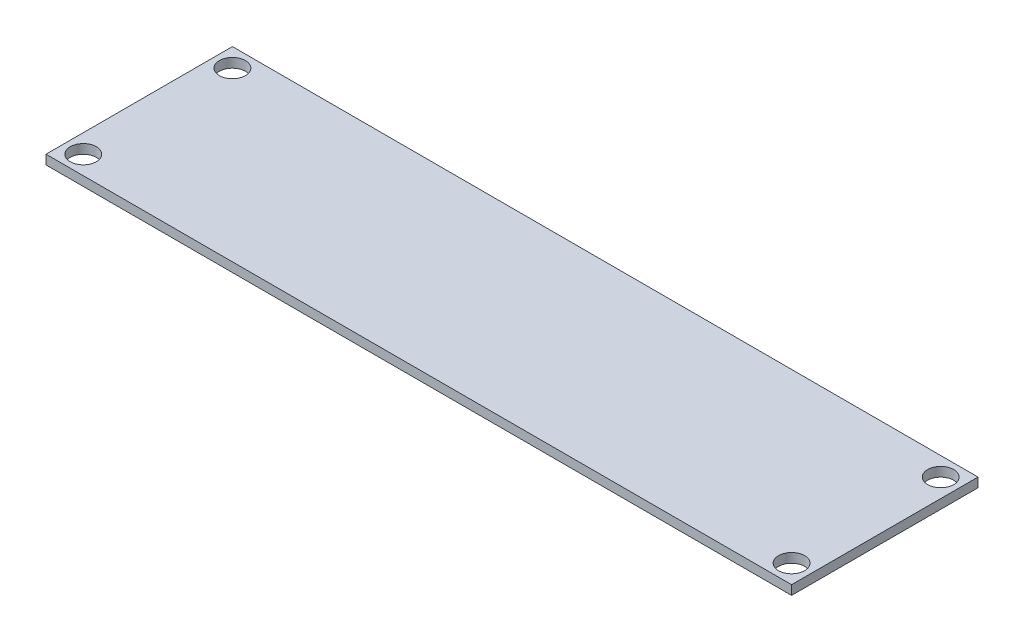
SolidWorks part; units mm, degrees
ref_plane "Front Plane" through (0, 0, 0) normal (0, 0, 1) x (1, 0, 0)
ref_plane "Top Plane" through (0, 0, 0) normal (0, 1, 0) x (1, 0, 0)
ref_plane "Right Plane" through (0, 0, 0) normal (1, 0, 0) x (0, 0, -1)
sketch "Sketch1" plane through (0, 0, 0) normal (0, 1, 0) x (1, 0, 0)
  line L1 (0, 0) -> (80, 0)
  line L2 (0, 0) -> (0, 20)
  line L3 (0, 20) -> (80, 20)
  line L4 (80, 0) -> (80, 20)
  dimension "D1" = 80
  dimension "D2" = 20
extrude "Boss-Extrude1" add sketch "Sketch1" along normal blind 1
sketch "Sketch2" plane through (0, 1, 0) normal (0, 1, 0) x (1, 0, 0)
  line L0 (2, 10) -> (0, 10) construction
  line L1 (2, 18) -> (78, 18) construction
  line L2 (2, 18) -> (2, 2) construction
  line L3 (2, 2) -> (78, 2) construction
  line L4 (78, 18) -> (78, 2) construction
  line L5 (0, 20) -> (0, 0) construction
  line L6 (40, 18) -> (40, 20) construction
  line L7 (80, 20) -> (0, 20) construction
  line L8 (40, 0) -> (40, 2) construction
  line L9 (0, 0) -> (80, 0) construction
  line L10 (78, 10) -> (80, 10) construction
  line L11 (80, 0) -> (80, 20) construction
  circle A0 centre (2, 18) radius 1.4
  circle A1 centre (78, 18) radius 1.4
  circle A2 centre (78, 2) radius 1.4
  circle A3 centre (2, 2) radius 1.4
  dimension "D3" = 2.8
  dimension "D1" = 2
  dimension "D2" = 2
extrude "Cut-Extrude1" cut sketch "Sketch2" against normal through all
